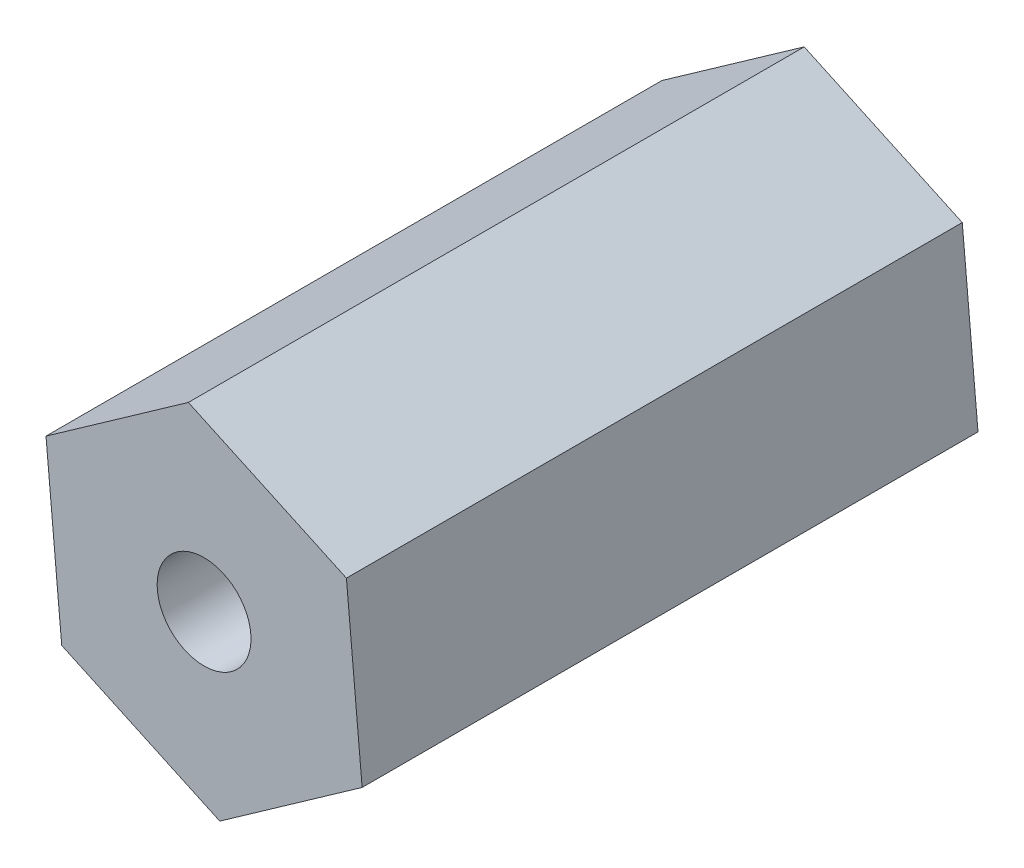
SolidWorks part; units mm, degrees
ref_plane "Front Plane" through (0, 0, 0) normal (0, 0, 1) x (1, 0, 0)
ref_plane "Top Plane" through (0, 0, 0) normal (0, 1, 0) x (1, 0, 0)
ref_plane "Right Plane" through (0, 0, 0) normal (1, 0, 0) x (0, 0, -1)
sketch "Sketch1" plane through (0, 0, 0) normal (0, 0, 1) x (1, 0, 0)
  line L1 (13.3644, -6.1816) -> (12.0356, 8.4831)
  line L2 (12.0356, 8.4831) -> (-1.3288, 14.6647)
  line L3 (-1.3288, 14.6647) -> (-13.3644, 6.1816)
  line L4 (-13.3644, 6.1816) -> (-12.0356, -8.4831)
  line L5 (-12.0356, -8.4831) -> (1.3288, -14.6647)
  line L6 (1.3288, -14.6647) -> (13.3644, -6.1816)
  circle A0 centre (0, 0) radius 12.752 construction
  point P1 (0, 0)
  dimension "D1" = 25.4
extrude "Boss-Extrude1" add sketch "Sketch1" along normal blind 52.07
hole_wizard "3/8-16 Tapped Hole1" positions "Sketch2" profile "Sketch3" tap size "3/8-16" standard "ANSI Inch" end condition through all
sketch "Sketch2" plane through (0, 0, 0) normal (0, 0, -1) x (-1, 0, 0)
  point P1 (0, 0)
sketch "Sketch3" plane through (0, 0, 0) normal (1, 0, 0) x (0, 1, 0)
  line L0 (0, 0) -> (0, 52.07)
  line L1 (0, 52.07) -> (3.9688, 52.07)
  line L2 (3.9688, 52.07) -> (3.9688, 1.4287)
  line L3 (3.9688, 1.4287) -> (5.3975, 0)
  line L5 (5.3975, 0) -> (0, 0)
  line L6 (-3.9688, 1.4287) -> (-5.3975, 0) construction
  line L11 (0, -6.35) -> (0, 107.95) construction
  dimension "Thru Tap Drill Dia." = 7.9375
  dimension "Thru Tap Drill Depth" = 52.07
  dimension "Near C'Sink Dia." = 10.795
  dimension "Near C'Sink Angle" = 90
cosmetic thread "Hole Thread1" parameters "D2"=9.525
